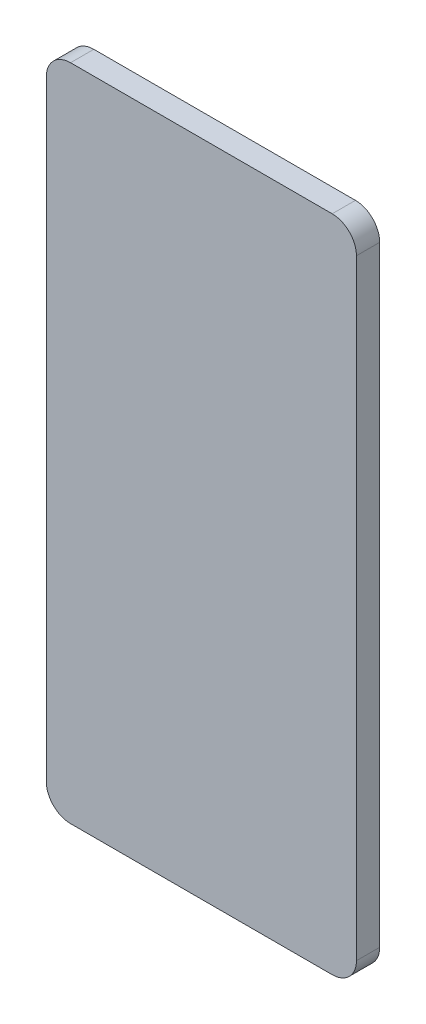
SolidWorks part; units mm, degrees
ref_plane "Front Plane" through (0, 0, 0) normal (0, 0, 1) x (1, 0, 0)
ref_plane "Top Plane" through (0, 0, 0) normal (0, 1, 0) x (1, 0, 0)
ref_plane "Right Plane" through (0, 0, 0) normal (1, 0, 0) x (0, 0, -1)
sketch "Sketch2" plane through (0, 0, 0) normal (0, 0, 1) x (1, 0, 0)
  line L0 (-14.2875, -35.9842) -> (14.2875, -35.9842)
  line L1 (-16.9342, -33.3375) -> (-16.9342, 33.3375)
  line L2 (14.2875, 35.9842) -> (-14.2875, 35.9842)
  line L3 (16.9342, 33.3375) -> (16.9342, -33.3375)
  line L4 (-14.2875, -38.1) -> (14.2875, -38.1)
  line L5 (-19.05, -33.3375) -> (-19.05, 33.3375)
  line L6 (14.2875, 38.1) -> (-14.2875, 38.1)
  line L7 (19.05, 33.3375) -> (19.05, -33.3375)
  line L8 (0, 0) -> (19.05, 0) construction
  line L9 (0, 0) -> (0, 38.1) construction
  arc A0 (19.05, 33.3375) -> (14.2875, 38.1) centre (14.2875, 33.3375) ccw
  arc A1 (14.2875, -38.1) -> (19.05, -33.3375) centre (14.2875, -33.3375) ccw
  arc A2 (-19.05, -33.3375) -> (-14.2875, -38.1) centre (-14.2875, -33.3375) ccw
  arc A3 (-14.2875, 38.1) -> (-19.05, 33.3375) centre (-14.2875, 33.3375) ccw
  arc A4 (-14.2875, 35.9842) -> (-16.9342, 33.3375) centre (-14.2875, 33.3375) ccw
  arc A5 (16.9342, 33.3375) -> (14.2875, 35.9842) centre (14.2875, 33.3375) ccw
  arc A6 (14.2875, -35.9842) -> (16.9342, -33.3375) centre (14.2875, -33.3375) ccw
  arc A7 (-16.9342, -33.3375) -> (-14.2875, -35.9842) centre (-14.2875, -33.3375) ccw
  point P3 (0, -38.1)
  point P4 (-19.05, 0)
  point P5 (0, 0)
  point P6 (19.05, -38.1)
  point P7 (-19.05, -38.1)
  point P8 (-19.05, 38.1)
  point P33 (0, 0)
  point P35 (19.05, 38.1)
  point P36 (19.05, 0)
  point P37 (0, 38.1)
  dimension "D1" = 4.7625
  dimension "Thickness" = 2.1158
  dimension "V_leg" = 76.2
  dimension "H_leg" = 38.1
extrude "Boss-Extrude1" add sketch "Sketch2" along normal blind 2.54 contours L1 A7 L0 A6 L3 A5 L2 A4
